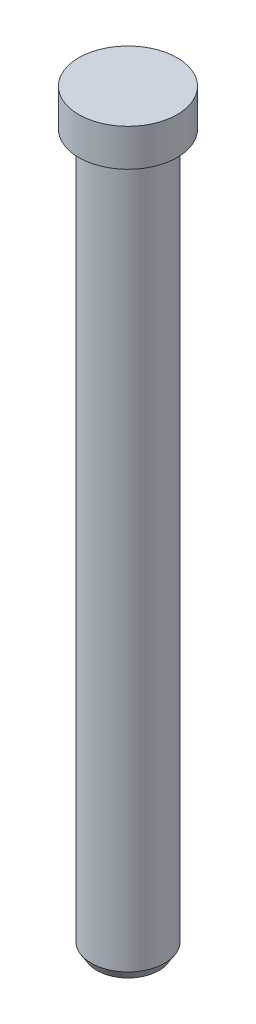
SolidWorks part; units mm, degrees
material "Acero al carbono no aleado"
ref_plane "Alzado" through (0, 0, 0) normal (0, 0, 1) x (1, 0, 0)
ref_plane "Planta" through (0, 0, 0) normal (0, 1, 0) x (1, 0, 0)
ref_plane "Vista lateral" through (0, 0, 0) normal (1, 0, 0) x (0, 0, -1)
sketch "Croquis1" plane through (0, 0, 0) normal (0, 0, 1) x (1, 0, 0)
  line L0 (0, 60.5) -> (7.9375, 60.5)
  line L1 (0, 60.5) -> (0, -60.5) construction
  line L2 (7.9375, 60.5) -> (7.9375, 54.5)
  line L3 (7.9375, 54.5) -> (5.9375, 54.5)
  line L4 (5.9375, 54.5) -> (5.9375, -59)
  line L5 (5.9375, -59) -> (5, -60.5)
  line L6 (5, -60.5) -> (0, -60.5)
  line L7 (0, -60.5) -> (0, 60.5)
  point P0 (0, 0)
  dimension "D1" = 7.9375
  dimension "D2" = 6
  dimension "D3" = 2
  dimension "D4" = 115
  dimension "D5" = 1.5
  dimension "D6" = 5
revolve "Revolución1" add sketch "Croquis1" angle 360 about L1
